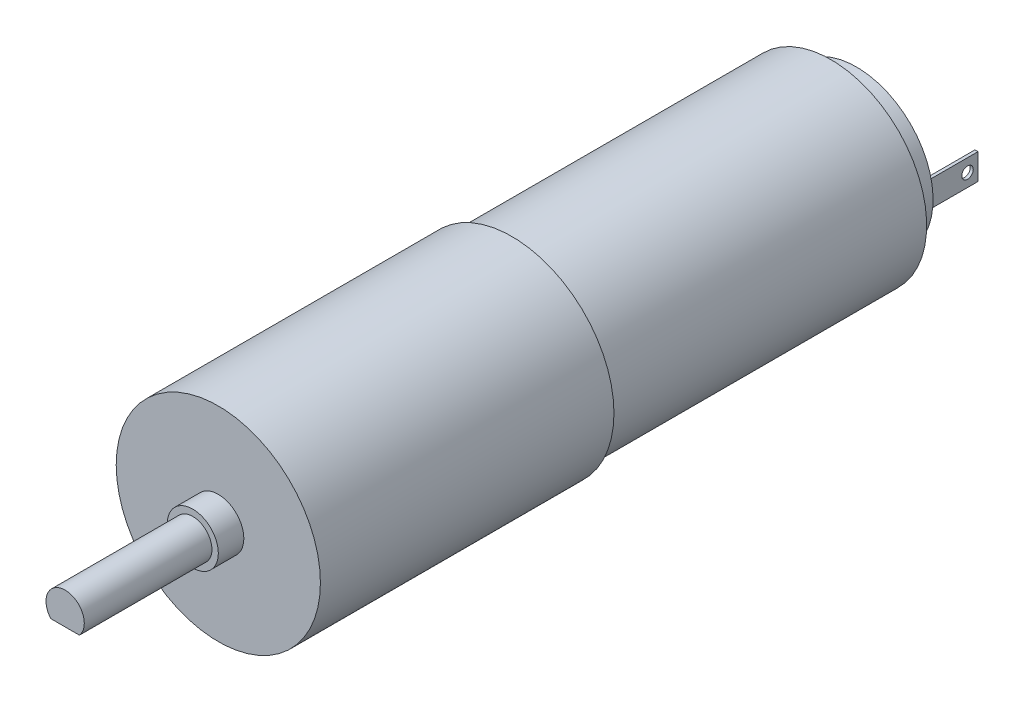
SolidWorks part; units mm, degrees
material "氧化铝"
ref_plane "前视基准面" through (0, 0, 0) normal (0, 0, 1) x (1, 0, 0)
ref_plane "上视基准面" through (0, 0, 0) normal (0, 1, 0) x (1, 0, 0)
ref_plane "右视基准面" through (0, 0, 0) normal (1, 0, 0) x (0, 0, -1)
other "Configuration Table"
sketch "草图1" plane through (0, 0, 0) normal (0, 0, 1) x (1, 0, 0)
  circle A0 centre (0, 0) radius 8
extrude "凸台-拉伸1" add sketch "草图1" along normal blind 23
sketch "草图2" plane through (0, 0, 0) normal (0, 0, -1) x (-1, 0, 0)
  circle A0 centre (0, 0) radius 6
extrude "凸台-拉伸2" add sketch "草图2" along normal blind 27
sketch "草图3" plane through (0, 0, 23) normal (0, 0, 1) x (1, 0, 0)
  circle A0 centre (0, 0) radius 1.5
extrude "凸台-拉伸3" add sketch "草图3" along normal blind 12
sketch "草图4" plane through (0, 0, 23) normal (0, 0, 1) x (1, 0, 0)
  circle A0 centre (0, 0) radius 2
extrude "凸台-拉伸4" add sketch "草图4" along normal blind 2
sketch "草图5" plane through (0, 0, 0) normal (0, 0, -1) x (-1, 0, 0)
  circle A0 centre (0, 0) radius 7.5
extrude "凸台-拉伸6" add sketch "草图5" along normal blind 25
sketch "草图6" plane through (0, 0, -25) normal (0, 0, -1) x (-1, 0, 0)
  line L0 (0, -6) -> (7.2519, -6)
  line L1 (7.2519, -6) -> (7.2519, -9)
  line L2 (7.2519, -9) -> (-7.0729, -9)
  line L3 (-7.0729, -9) -> (-7.0729, -6)
  line L4 (-7.0729, -6) -> (0, -6)
  circle A0 centre (0, 0) radius 6 construction
  circle A1 centre (0, 0) radius 6 construction
extrude "切除-拉伸2" cut sketch "草图6" against normal blind 25
sketch "草图7" plane through (0, 0, -27) normal (0, 0, -1) x (-1, 0, 0)
  line L1 (-5.521, -1.0147) -> (-5.2823, -1.0147)
  line L2 (-5.521, -1.0147) -> (-5.521, 1.0147)
  line L3 (-5.521, 1.0147) -> (-5.2823, 1.0147)
  line L4 (-5.2823, -1.0147) -> (-5.2823, 1.0147)
  line L5 (-5.521, -1.0147) -> (-5.2823, 1.0147) construction
  line L6 (-5.521, 1.0147) -> (-5.2823, -1.0147) construction
  line L7 (5.2674, -1.0147) -> (5.4763, -1.0147)
  line L8 (5.2674, -1.0147) -> (5.2674, 1.0147)
  line L9 (5.2674, 1.0147) -> (5.4763, 1.0147)
  line L10 (5.4763, -1.0147) -> (5.4763, 1.0147)
  line L11 (5.2674, -1.0147) -> (5.4763, 1.0147) construction
  line L12 (5.2674, 1.0147) -> (5.4763, -1.0147) construction
  point P0 (-5.4016, 0)
  point P5 (5.3718, 0)
extrude "凸台-拉伸7" add sketch "草图7" along normal blind 4
sketch "草图8" plane through (5.521, 0, 0) normal (1, 0, 0) x (0, 0, -1)
  circle A0 centre (30.1779, 0) radius 0.4518
extrude "切除-拉伸3" cut sketch "草图8" against normal blind 40
sketch "草图9" plane through (0, 0, 35) normal (0, 0, 1) x (1, 0, 0)
  line L1 (-2.2979, -1.5369) -> (2.2979, -1.5369)
  line L2 (-2.2979, -1.5369) -> (-2.2979, -0.9998)
  line L3 (-2.2979, -0.9998) -> (2.2979, -0.9998)
  line L4 (2.2979, -1.5369) -> (2.2979, -0.9998)
  line L5 (-2.2979, -1.5369) -> (2.2979, -0.9998) construction
  line L6 (-2.2979, -0.9998) -> (2.2979, -1.5369) construction
  point P0 (0, -1.2683)
extrude "切除-拉伸4" cut sketch "草图9" against normal blind 6
